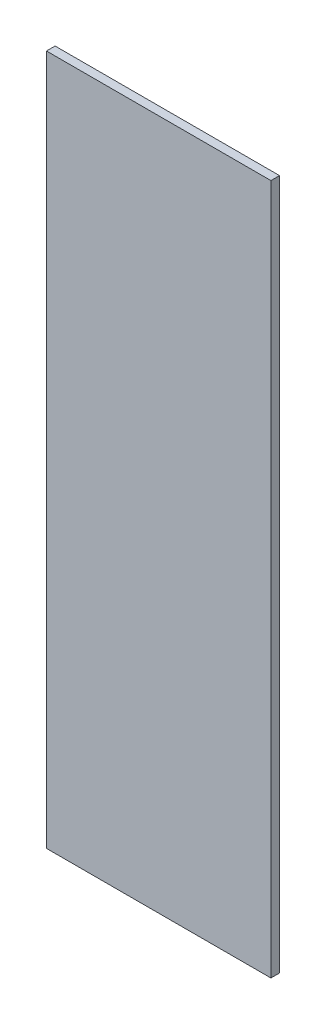
SolidWorks part; units mm, degrees
material "1.0037 (S235JR)"
ref_plane "Plan de face" through (0, 0, 0) normal (0, 0, 1) x (1, 0, 0)
ref_plane "Plan de dessus" through (0, 0, 0) normal (0, 1, 0) x (1, 0, 0)
ref_plane "Plan de droite" through (0, 0, 0) normal (1, 0, 0) x (0, 0, -1)
sketch "Esquisse1" plane through (0, 0, 0) normal (0, 0, 1) x (1, 0, 0)
  line L1 (65, -200) -> (-65, -200)
  line L2 (65, -200) -> (65, 200)
  line L3 (65, 200) -> (-65, 200)
  line L4 (-65, -200) -> (-65, 200)
  line L5 (65, -200) -> (-65, 200) construction
  line L6 (65, 200) -> (-65, -200) construction
  point P0 (0, 0)
  dimension "D1" = 400
  dimension "D2" = 130
extrude "Boss.-Extru.1" add sketch "Esquisse1" along normal blind 5
